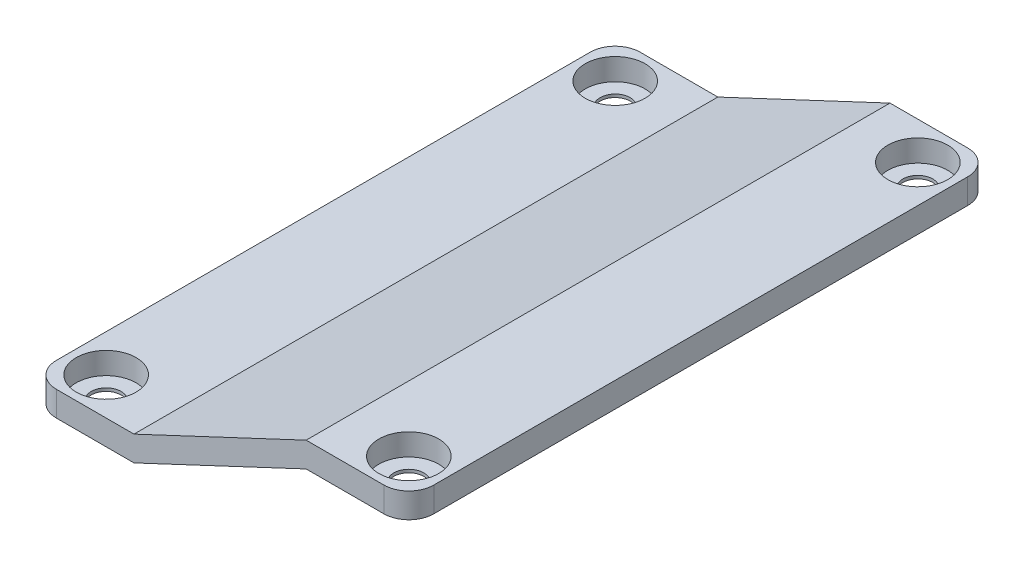
SolidWorks part; units mm, degrees
ref_plane "Front Plane" through (0, 0, 0) normal (0, 0, 1) x (1, 0, 0)
ref_plane "Top Plane" through (0, 0, 0) normal (0, 1, 0) x (1, 0, 0)
ref_plane "Right Plane" through (0, 0, 0) normal (1, 0, 0) x (0, 0, -1)
sketch "Sketch1" plane through (0, 0, 0) normal (0, 0, 1) x (1, 0, 0)
  line L0 (-17.5078, -4.569) -> (16.9922, 11.631)
  line L1 (-17.5078, -9.569) -> (-38.0828, -9.569)
  line L2 (-17.5078, -4.569) -> (-38.0828, -4.569)
  line L3 (-38.0828, -9.569) -> (-38.0828, -4.569)
  line L4 (16.9922, 6.631) -> (37.5672, 6.631)
  line L5 (16.9922, 11.631) -> (37.5672, 11.631)
  line L6 (37.5672, 6.631) -> (37.5672, 11.631)
  line L7 (-17.5078, -9.569) -> (16.9922, 6.631)
  dimension "D1" = 20.575
  dimension "D2" = 20.575
  dimension "D3" = 75.65
  dimension "D4" = 21.2
extrude "Cover Body" add sketch "Sketch1" against normal blind 117
sketch "Screw Hole outlines" plane through (0, -4.569, 0) normal (0, 1, 0) x (1, 0, 0)
  line L0 (16.9922, 117) -> (-17.5078, 117) construction
  line L1 (-30.5828, 109.5) -> (29.0672, 109.5) construction
  line L2 (-30.5828, 109.5) -> (-30.5828, 7.5) construction
  line L3 (-30.5828, 7.5) -> (29.0672, 7.5) construction
  line L4 (29.0672, 109.5) -> (29.0672, 7.5) construction
  line L5 (-38.0828, 117) -> (-38.0828, 0) construction
  line L6 (37.5672, 117) -> (37.5672, 0) construction
  line L8 (37.5672, 0) -> (16.9922, 0) construction
  dimension "D1" = 7.5
  dimension "D2" = 8.5
  dimension "D3" = 7.5
  dimension "7.5" = 7.5
hole_wizard "CBORE for M6 Hex Head Bolt1" positions "Sketch2" profile "Sketch4" counterbore size "M6" standard "ANSI Metric" end condition through all
sketch "Sketch2" plane through (0, -4.569, 0) normal (0, 1, 0) x (1, 0, 0)
  line L0 (-38.0828, 117) -> (-38.0828, 0) construction
  line L1 (-17.5078, 0) -> (-38.0828, 0) construction
  line L2 (-17.5078, 117) -> (-38.0828, 117) construction
  point P0 (-30.5828, 109.5)
  point P3 (-30.5828, 7.5)
  dimension "D1" = 7.5
  dimension "D2" = 7.5
  dimension "D3" = 7.5
  dimension "D4" = 7.5
sketch "Sketch4" plane through (-30.5828, -4.569, -109.5) normal (1, 0, 0) x (0, 0, 1)
  line L0 (0, 0) -> (0, 5)
  line L1 (0, 5) -> (3, 5)
  line L3 (3, 5) -> (3, 4.38)
  line L4 (3, 4.38) -> (6, 4.38)
  line L5 (6, 4.38) -> (6, 0)
  line L7 (6, 0) -> (0, 0)
  line L11 (0, -6.35) -> (0, 107.95) construction
  dimension "Thru Hole Dia." = 6
  dimension "Thru Hole Depth" = 5
  dimension "C'Bore Dia." = 12
  dimension "C'Bore Depth" = 4.38
ref_plane "Upper Lid Plane" through (29.0672, 0, 0) normal (1, 0, 0) x (0, 0, -1)
sketch "Sketch9" plane through (29.0672, 0, 0) normal (1, 0, 0) x (0, 0, -1)
  line L0 (8.5, -4.569) -> (8.5, 11.631) construction
  line L1 (109.5, -4.569) -> (7.5, -4.569) construction
  line L2 (109.5, -4.569) -> (7.5, -4.569) construction
  line L3 (117, 11.631) -> (0, 11.631) construction
  line L4 (85.5, -4.569) -> (85.5, 11.631) construction
  dimension "D1" = 77
hole_wizard "CBORE for M6 Hex Head Bolt2" positions "Sketch10" profile "Sketch11" counterbore size "M6" standard "ANSI Metric" end condition up to next
sketch "Sketch10" plane through (0, 11.631, 0) normal (0, 1, 0) x (1, 0, 0)
  line L0 (-30.5828, 109.5) -> (39.7843, 109.5) construction
  line L2 (30.0672, 115.1486) -> (30.0672, -7.1503) construction
  line L4 (37.5672, 117) -> (37.5672, 0) construction
  line L5 (37.5672, 0) -> (16.9922, 0) construction
  point P0 (30.0672, 7.5)
  point P19 (30.0672, 109.5)
  dimension "D1" = 102
  dimension "D2" = 7.5
  dimension "D3" = 7.5
sketch "Sketch11" plane through (30.0672, 11.631, -7.5) normal (1, 0, 0) x (0, 0, 1)
  line L0 (0, 0) -> (0, 5)
  line L1 (0, 5) -> (3, 5)
  line L3 (3, 5) -> (3, 4.38)
  line L4 (3, 4.38) -> (6, 4.38)
  line L5 (6, 4.38) -> (6, 0)
  line L7 (6, 0) -> (0, 0)
  line L11 (0, -6.35) -> (0, 107.95) construction
  dimension "Thru Hole Dia." = 6
  dimension "Thru Hole Depth" = 5
  dimension "C'Bore Dia." = 12
  dimension "C'Bore Depth" = 4.38
fillet "Fillet1" radius 5 4 edges at (-38.0828, -7.069, -117) (37.5672, 9.131, -117) (37.5672, 9.131, 0) (-38.0828, -7.069, 0)
